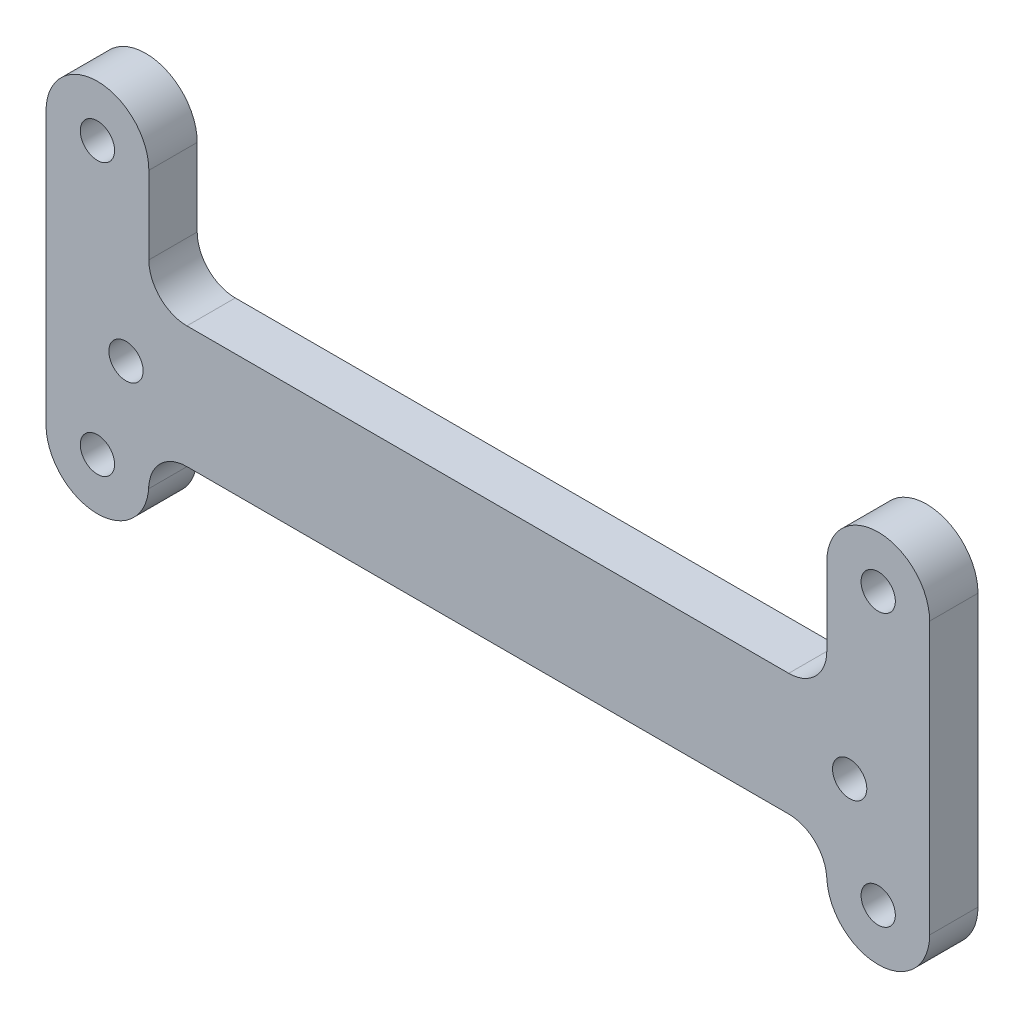
SolidWorks part; units mm, degrees
material "ABS"
ref_plane "Front Plane" through (0, 0, 0) normal (0, 0, 1) x (1, 0, 0)
ref_plane "Top Plane" through (0, 0, 0) normal (0, 1, 0) x (1, 0, 0)
ref_plane "Right Plane" through (0, 0, 0) normal (1, 0, 0) x (0, 0, -1)
sketch "Sketch2" plane through (0, 0, 71.255) normal (0, 0, -1) x (-1, 0, 0)
  line L2 (-47.5, -8) -> (47.5, -8)
  line L3 (47.5, 8) -> (-47.5, 8)
  line L4 (-39.5, -8) -> (39.5, -8)
  line L5 (39.5, 8) -> (-39.5, 8)
  line L6 (58, 23.184) -> (58, -12.4964)
  line L7 (-58, -12.4964) -> (-58, 23.184)
  line L8 (44.5, -12.4964) -> (44.5, -13)
  line L9 (-44.5248, -13.0739) -> (-44.4817, -12.5722)
  line L10 (-47.5, -8) -> (47.5, -8) construction
  line L11 (44.5, 23.184) -> (44.5, 13)
  line L12 (-44.5, 23.184) -> (-44.5, 13)
  circle A0 centre (47.5, 0) radius 2.25 construction
  circle A1 centre (-47.5, 0) radius 2.25 construction
  arc A2 (-47.5, 8) -> (-47.5, -8) centre (-47.5, 0) ccw
  arc A3 (47.5, -8) -> (47.5, 8) centre (47.5, 0) ccw
  circle A6 centre (47.5, 0) radius 2.25
  circle A7 centre (-47.5, 0) radius 2.25
  arc A8 (44.5, -12.4964) -> (58, -12.4964) centre (51.25, -12.4964) ccw
  arc A9 (58, 23.184) -> (44.5, 23.184) centre (51.25, 23.184) ccw
  arc A10 (-44.5, 23.184) -> (-58, 23.184) centre (-51.25, 23.184) ccw
  arc A11 (-58, -12.4964) -> (-44.5248, -13.0739) centre (-51.25, -12.4964) ccw
  circle A12 centre (51.25, 23.184) radius 2.25 construction
  circle A13 centre (51.25, -12.4964) radius 2.25 construction
  circle A14 centre (-51.25, -12.4964) radius 2.25 construction
  circle A15 centre (-51.25, 23.184) radius 2.25 construction
  arc A18 (54.5148, -31.5775) -> (-54.5148, -31.5775) centre (0, 0) ccw construction
  arc A19 (-44.5, 13) -> (-39.5, 8) centre (-39.5, 13) ccw
  arc A20 (-44.4817, -12.5722) -> (-39.5, -8) centre (-39.5, -13) cw
  arc A21 (44.5, -13) -> (39.5, -8) centre (39.5, -13) ccw
  arc A22 (44.5, 13) -> (39.5, 8) centre (39.5, 13) cw
  circle A23 centre (51.25, 23.184) radius 2.25
  circle A24 centre (51.25, -12.4964) radius 2.25
  circle A25 centre (-51.25, -12.4964) radius 2.25
  circle A26 centre (-51.25, 23.184) radius 2.25
  point P53 (44.5, -8)
  dimension "D2" = 5
  dimension "D1" = 0
extrude "Boss-Extrude1" add sketch "Sketch2" along normal blind 6.35
